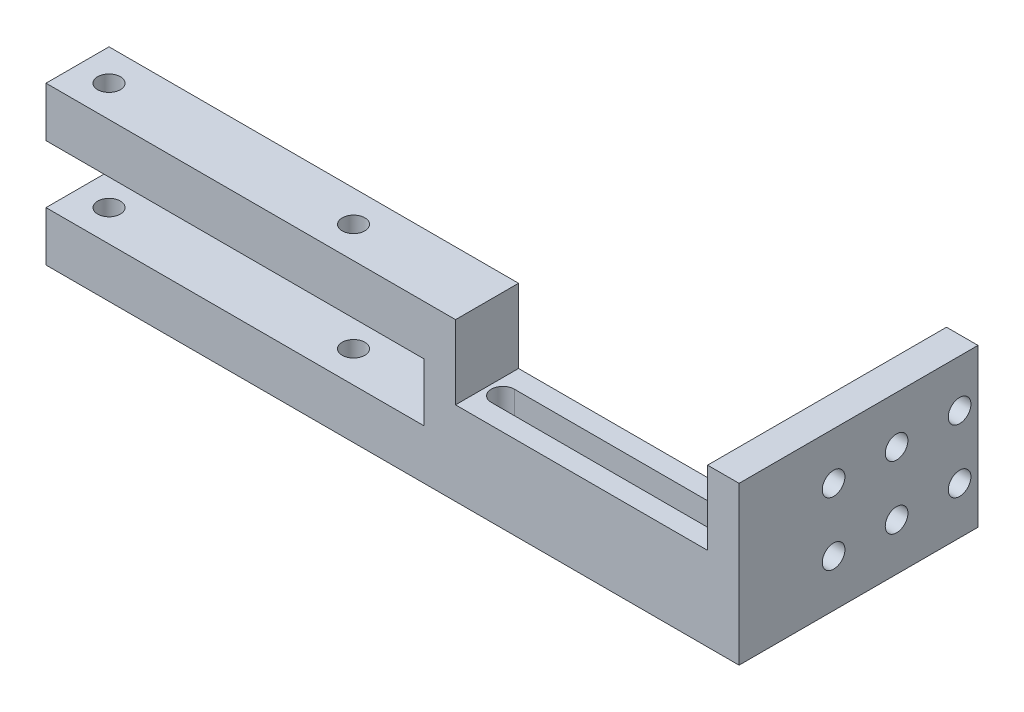
SolidWorks part; units mm, degrees
material "ABS"
ref_plane "Front Plane" through (0, 0, 0) normal (0, 0, 1) x (1, 0, 0)
ref_plane "Top Plane" through (0, 0, 0) normal (0, 1, 0) x (1, 0, 0)
ref_plane "Right Plane" through (0, 0, 0) normal (1, 0, 0) x (0, 0, -1)
sketch "Sketch1" plane through (0, 0, 0) normal (0, 1, 0) x (1, 0, 0)
  line L0 (0, 0) -> (110, 0)
  line L1 (0, 10) -> (110, 10)
  line L2 (0, 10) -> (0, 0)
  line L3 (110, 10) -> (110, 0)
  circle A0 centre (5, 5) radius 1.8
  circle A1 centre (43.81, 5) radius 1.8
  dimension "D4" = 3.6
  dimension "D7" = 3.6
  dimension "D1" = 110
  dimension "D2" = 110
  dimension "D3" = 10
  dimension "D5" = 5
  dimension "D6" = 5
  dimension "D8" = 5
  dimension "D9" = 38.81
extrude "Boss-Extrude1" add sketch "Sketch1" along normal blind 25
sketch "Sketch2" plane through (0, 0, 0) normal (-1, 0, 0) x (0, 0, 1)
  line L0 (-10, 7.9) -> (0, 7.9)
  line L1 (-10, 25) -> (-10, 0) construction
  line L2 (0, 25) -> (0, 0) construction
  line L3 (-10, 17.1) -> (0, 17.1)
  line L4 (-10, 0) -> (0, 0) construction
  line L5 (-10, 25) -> (0, 25) construction
  line L6 (0, 7.9) -> (0, 17.1)
  line L7 (-10, 7.9) -> (-10, 17.1)
  point P10 (-5, 25)
  dimension "D1" = 7.9
  dimension "D2" = 7.9
extrude "Cut-Extrude1" cut sketch "Sketch2" against normal blind 60
sketch "Sketch16" plane through (0, 0, -10) normal (0, 0, -1) x (-1, 0, 0)
  line L0 (-105, 0) -> (-105, 25)
  line L1 (0, 0) -> (-110, 0) construction
  line L2 (0, 25) -> (-110, 25) construction
  line L3 (-110, 25) -> (-110, 0) construction
  line L4 (-105, 25) -> (-110, 25)
  line L5 (-110, 25) -> (-110, 0)
  line L6 (-110, 0) -> (-105, 0)
  line L12 (-60, 17.1) -> (0, 17.1)
  line L13 (0, 17.1) -> (0, 25)
  line L14 (0, 25) -> (-110, 25)
  line L15 (-110, 25) -> (-110, 0)
  line L16 (-110, 0) -> (0, 0)
  line L17 (0, 0) -> (0, 7.9)
  line L18 (0, 7.9) -> (-60, 7.9)
  line L19 (-60, 7.9) -> (-60, 17.1)
  line L20 (-60, 17.1) -> (0, 17.1)
  line L21 (0, 17.1) -> (0, 25)
  line L22 (0, 25) -> (-105, 25)
  line L24 (-105, 0) -> (0, 0)
  line L25 (0, 0) -> (0, 7.9)
  line L26 (0, 7.9) -> (-60, 7.9)
  line L27 (-60, 7.9) -> (-60, 17.1)
  line M11 (0, 25) -> (-110, 25)
  line M12 (-110, 25) -> (-110, 0)
  line M13 (-110, 0) -> (0, 0)
  dimension "D1" = 5
  dimension "D2" = 0
extrude "Boss-Extrude2" add sketch "Sketch16" along normal blind 10 contours L0 M13 M11 M12
sketch "Sketch17" plane through (110, 0, 0) normal (1, 0, 0) x (0, 0, -1)
  line L1 (20, 25) -> (20, 0) construction
  line L3 (0, 25) -> (0, 0) construction
  line L4 (0, 12.5) -> (20, 12.5) construction
  circle A0 centre (15, 7.5) radius 1.8
  circle A1 centre (15, 17.5) radius 1.8
  point P4 (0, 12.5)
  dimension "D1" = 3.6
  dimension "D2" = 3.6
  dimension "D5" = 5
  dimension "D3" = 5
  dimension "D4" = 0
  dimension "D6" = 5
extrude "Cut-Extrude6" cut sketch "Sketch17" against normal blind 10
sketch "Sketch18" plane through (0, 0, -20) normal (0, 0, -1) x (-1, 0, 0)
  line L0 (-110, 0) -> (-105, 0) construction
  line L1 (-110, 25) -> (-105, 25)
  line L2 (-110, 25) -> (-110, 0)
  line L3 (-110, 0) -> (-105, 0)
  line L4 (-105, 25) -> (-105, 0)
  line L5 (-105, 0) -> (-105, 25) construction
extrude "Boss-Extrude3" add sketch "Sketch18" along normal blind 20
sketch "Sketch19" plane through (105, 0, 0) normal (-1, 0, 0) x (0, 0, 1)
  circle A0 centre (-25, 17.5) radius 1.8
  circle A1 centre (-25, 7.5) radius 1.8
  circle A2 centre (-35, 17.5) radius 1.8
  circle A3 centre (-35, 7.5) radius 1.8
  circle A4 centre (-15, 17.5) radius 1.8 construction
  circle A5 centre (-15, 7.5) radius 1.8 construction
  dimension "D5" = 3.6
  dimension "D6" = 3.6
  dimension "D1" = 3.6
  dimension "D2" = 3.6
  dimension "D3" = 10
  dimension "D4" = 10
  dimension "D7" = 10
  dimension "D8" = 10
  dimension "D9" = 10
  dimension "D10" = 10
extrude "Cut-Extrude7" cut sketch "Sketch19" against normal blind 12
sketch "Sketch20" plane through (0, 0, 0) normal (0, -1, 0) x (1, 0, 0)
  line L0 (110, -40) -> (110, 0) construction
  line L1 (110, -37.9215) -> (105, -37.9215)
  line L2 (110, -37.9215) -> (110, -40)
  line L3 (110, -40) -> (105, -40)
  line L4 (105, -37.9215) -> (105, -40)
extrude "Cut-Extrude8" cut sketch "Sketch20" against normal blind 46
sketch "Sketch21" plane through (0, 25, 0) normal (0, 1, 0) x (1, 0, 0)
  line L0 (0, 0) -> (110, 0) construction
  line L1 (105, 10) -> (65, 10)
  line L2 (105, 10) -> (105, 0)
  line L3 (105, 0) -> (65, 0)
  line L4 (65, 10) -> (65, 0)
  dimension "D1" = 40
extrude "Cut-Extrude9" cut sketch "Sketch21" against normal blind 11.715
sketch "Sketch23" plane through (0, 13.285, 0) normal (0, 1, 0) x (1, 0, 0)
  line L0 (105, 5) -> (65, 5) construction
  line L1 (105, 0) -> (105, 10) construction
  line L2 (65, 10) -> (65, 0) construction
  line L3 (67.5, 5) -> (102.5, 5) construction
  line L4 (67.5, 6.825) -> (102.5, 6.825)
  line L5 (67.5, 3.175) -> (102.5, 3.175)
  arc A0 (67.5, 6.825) -> (67.5, 3.175) centre (67.5, 5) ccw
  arc A1 (102.5, 3.175) -> (102.5, 6.825) centre (102.5, 5) ccw
  point P8 (85, 5)
  dimension "D1" = 1.825
  dimension "D2" = 35
extrude "Cut-Extrude10" cut sketch "Sketch23" against normal up to surface (13.285 mm away) up to face at (43.81, 0, -3.2)
